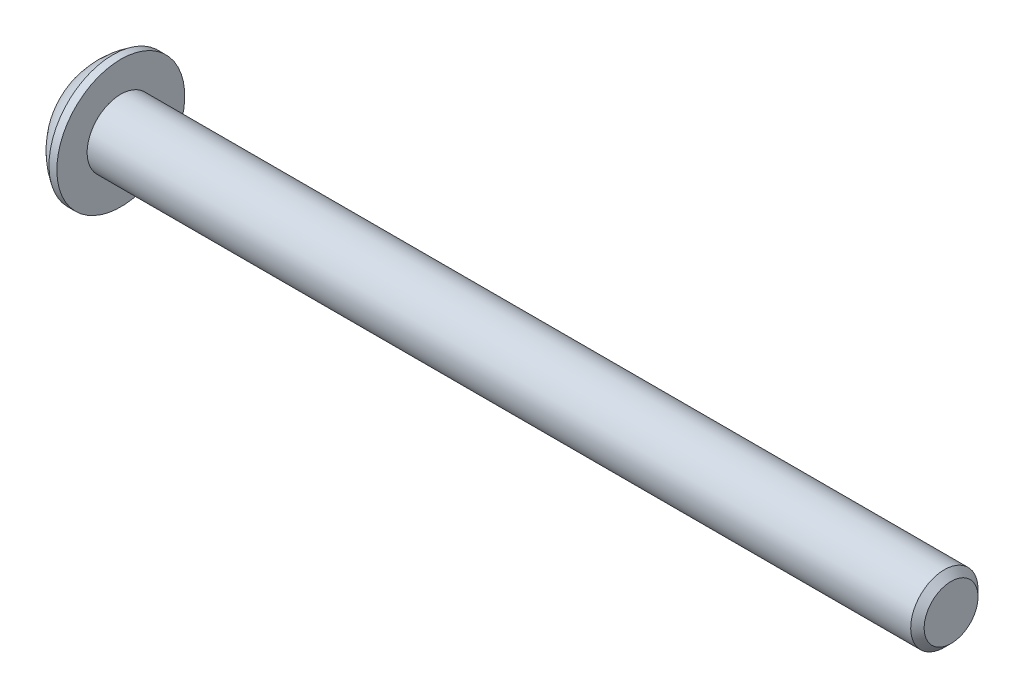
SolidWorks part; units mm, degrees
ref_plane "Front Plane" through (0, 0, 0) normal (0, 0, 1) x (1, 0, 0)
ref_plane "Top Plane" through (0, 0, 0) normal (0, 1, 0) x (1, 0, 0)
ref_plane "Right Plane" through (0, 0, 0) normal (1, 0, 0) x (0, 0, -1)
sketch "Sketch1" plane through (0, 0, 0) normal (0, 0, 1) x (1, 0, 0)
  line L0 (38.65, 0) -> (0, 0)
  line L2 (1.65, 2.85) -> (1.65, 1.5)
  line L3 (1.65, 1.5) -> (38.65, 1.5)
  line L4 (38.65, 1.5) -> (38.65, 0)
  line L5 (1.65, 2.85) -> (1.3, 2.85)
  line L6 (0, 0) -> (0, 1.425)
  arc A3 (0, 1.425) -> (1.3, 2.85) centre (3.1356, -0.13) cw
  dimension "D7" = 3.5
  dimension "D1" = 37
  dimension "D2" = 1.5
  dimension "D3" = 2.85
  dimension "D4" = 0.35
  dimension "D5" = 1.65
  dimension "D6" = 1.425
revolve "Revolve1" add sketch "Sketch1" angle 360 about L0
chamfer "Chamfer1" distance 0.3 angle 45 1 edges at (38.65, 1.5, 0)
sketch "Sketch2" plane through (0, 0, 0) normal (-1, 0, 0) x (0, 0, 1)
  line L1 (0, 1.1547) -> (-1, 0.5774)
  line L2 (-1, 0.5774) -> (-1, -0.5774)
  line L3 (-1, -0.5774) -> (0, -1.1547)
  line L4 (0, -1.1547) -> (1, -0.5774)
  line L5 (1, -0.5774) -> (1, 0.5774)
  line L6 (1, 0.5774) -> (0, 1.1547)
  circle A0 centre (0, 0) radius 1 construction
  dimension "D1" = 2
extrude "Cut-Extrude1" cut sketch "Sketch2" against normal blind 1
